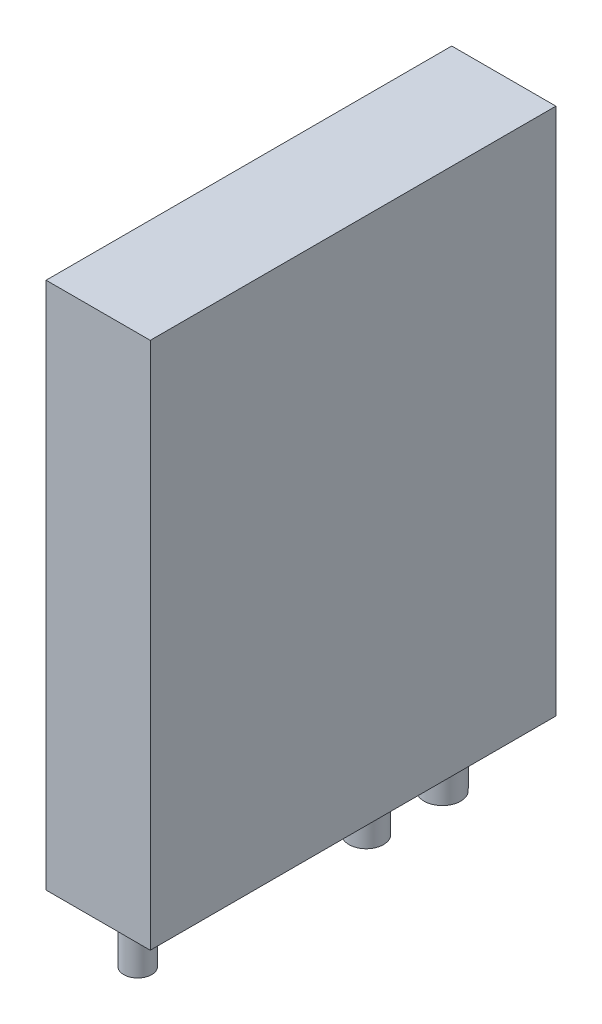
SolidWorks part; units mm, degrees
ref_plane "Front Plane" through (0, 0, 0) normal (0, 0, 1) x (1, 0, 0)
ref_plane "Top Plane" through (0, 0, 0) normal (0, 1, 0) x (1, 0, 0)
ref_plane "Right Plane" through (0, 0, 0) normal (1, 0, 0) x (0, 0, -1)
sketch "Sketch1" plane through (0, 0, 0) normal (1, 0, 0) x (0, 0, -1)
  line L1 (-10.145, -13.21) -> (10.145, -13.21)
  line L2 (-10.145, -13.21) -> (-10.145, 13.21)
  line L3 (-10.145, 13.21) -> (10.145, 13.21)
  line L4 (10.145, -13.21) -> (10.145, 13.21)
  line L5 (-10.145, -13.21) -> (10.145, 13.21) construction
  line L6 (-10.145, 13.21) -> (10.145, -13.21) construction
  point P0 (0, 0)
  dimension "D1" = 20.29
  dimension "D2" = 26.42
extrude "Boss-Extrude1" add sketch "Sketch1" along normal blind 5.21
sketch "Sketch2" plane through (0, -13.21, 0) normal (0, -1, 0) x (1, 0, 0)
  line L0 (2.605, -10.145) -> (2.605, 10.145) construction
  line L1 (5.21, -10.145) -> (0, -10.145) construction
  line L2 (5.21, 10.145) -> (0, 10.145) construction
  circle A0 centre (2.605, -7.0739) radius 0.915
  circle A1 centre (2.605, -3.2639) radius 0.865
  circle A2 centre (2.605, 8.1661) radius 0.7
  dimension "D1" = 1.83
  dimension "D2" = 1.73
  dimension "D3" = 1.4
  dimension "D5" = 11.43
  dimension "D4" = 3.81
extrude "Boss-Extrude2" add sketch "Sketch2" along normal blind 3
